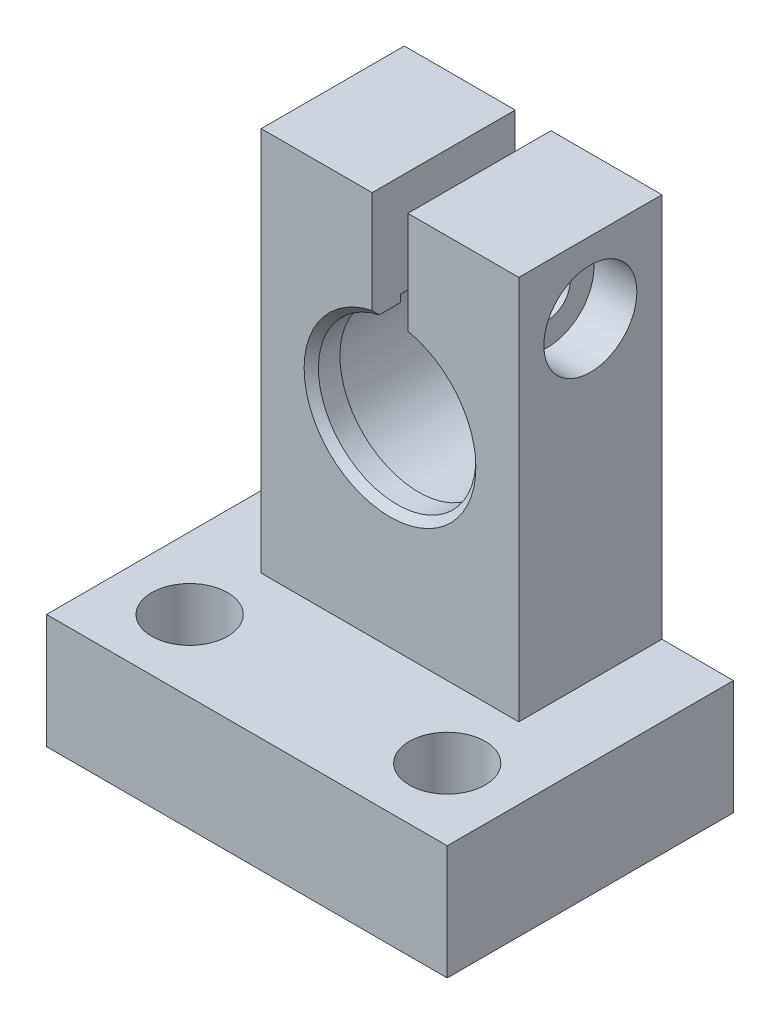
SolidWorks part; units mm, degrees
material "AISI 1045 Steel, cold drawn"
ref_plane "Front Plane" through (0, 0, 0) normal (0, 0, 1) x (1, 0, 0)
ref_plane "Top Plane" through (0, 0, 0) normal (0, 1, 0) x (1, 0, 0)
ref_plane "Right Plane" through (0, 0, 0) normal (1, 0, 0) x (0, 0, -1)
sketch "Sketch1" plane through (0, 0, 0) normal (0, 0, 1) x (1, 0, 0)
  line L1 (9, -21.9) -> (-9, -21.9)
  line L2 (9, -21.9) -> (9, 13)
  line L3 (9, 13) -> (-9, 13)
  line L4 (-9, -21.9) -> (-9, 13)
  line L5 (9, -21.9) -> (-9, 13) construction
  line L6 (9, 13) -> (-9, -21.9) construction
  circle A0 centre (0, 0) radius 6
  point P3 (0, -4.45)
  dimension "D1" = 12
  dimension "D2" = 13
  dimension "D3" = 21.9
  dimension "D4" = 18
extrude "Boss-Extrude1" add sketch "Sketch1" along normal blind 10
sketch "Sketch2" plane through (0, 0, 10) normal (0, 0, -1) x (-1, 0, 0)
  circle A0 centre (0, 0) radius 6 construction
  circle A1 centre (0, 0) radius 6
  circle A2 centre (0, 0) radius 5.5
  dimension "D1" = 0.5
extrude "Boss-Extrude2" add sketch "Sketch2" along normal blind 2
sketch "Sketch3" plane through (0, 0, 10) normal (0, 0, 1) x (1, 0, 0)
  line L0 (9, 13) -> (-9, 13) construction
  line L1 (1.25, 5.3561) -> (-1.25, 5.3561)
  line L2 (1.25, 5.3561) -> (1.25, 13)
  line L3 (1.25, 13) -> (-1.25, 13)
  line L4 (-1.25, 5.3561) -> (-1.25, 13)
  line L5 (1.25, 5.3561) -> (-1.25, 13) construction
  line L6 (1.25, 13) -> (-1.25, 5.3561) construction
  circle A0 centre (0, 0) radius 5.5 construction
  point P0 (0, 9.178)
  dimension "D1" = 2.5
extrude "Cut-Extrude1" cut sketch "Sketch3" against normal through all
hole_wizard "CBORE for M3 SHCS1" positions "Sketch4" profile "Sketch5" counterbore size "M3" standard "ANSI Metric"
sketch "Sketch4" plane through (9, 0, 0) normal (1, 0, 0) x (0, 0, -1)
  line L0 (0, -21.9) -> (0, 13) construction
  line L1 (-10, 13) -> (0, 13) construction
  point P0 (-5, 8)
  dimension "D1" = 5
  dimension "D2" = 5
sketch "Sketch5" plane through (9, 8, 5) normal (0, 1, 0) x (0, 0, -1)
  line L0 (0, 0) -> (0, 7.75)
  line L1 (0, 7.75) -> (1.6, 7.75)
  line L3 (1.6, 7.75) -> (1.6, 3)
  line L4 (1.6, 3) -> (3.25, 3)
  line L5 (3.25, 3) -> (3.25, 0)
  line L7 (3.25, 0) -> (0, 0)
  line L11 (0, -6.35) -> (0, 107.95) construction
  dimension "Thru Hole Dia." = 3.2
  dimension "Thru Hole Depth" = 7.75
  dimension "C'Bore Dia." = 6.5
  dimension "C'Bore Depth" = 3
hole_wizard "Tap Drill for M3x0.5 Tap1" positions "Sketch6" profile "Sketch7" hole size "M3x0.5" standard "ANSI Metric" end condition up to next
sketch "Sketch6" plane through (-9, 0, 0) normal (-1, 0, 0) x (0, 0, 1)
  line L0 (10, 13) -> (10, -21.9) construction
  line L1 (10, 13) -> (0, 13) construction
  point P0 (5, 8)
  dimension "D1" = 5
  dimension "D2" = 5
sketch "Sketch7" plane through (-9, 8, 5) normal (0, 1, 0) x (0, 0, 1)
  line L0 (0, 0) -> (0, 7.75)
  line L1 (0, 7.75) -> (1.25, 7.75)
  line L2 (1.25, 7.75) -> (1.25, 0)
  line L5 (1.25, 0) -> (0, 0)
  line L11 (0, -6.35) -> (0, 107.95) construction
  dimension "Thru Hole Dia." = 2.5
  dimension "Thru Hole Depth" = 7.75
chamfer "Chamfer1" distance 0.5 angle 45 2 edges at (0, -5.5, 10) (0, -6, 0)
sketch "Sketch11" plane through (-9, 0, 0) normal (-1, 0, 0) x (0, 0, 1)
  line L0 (0, 13) -> (0, -21.9) construction
  line L1 (0, -21.9) -> (10, -21.9)
  line L2 (0, -21.9) -> (0, -13.9)
  line L3 (0, -13.9) -> (10, -13.9)
  line L4 (10, -21.9) -> (10, -13.9)
  line L5 (10, 13) -> (10, -21.9) construction
  dimension "D1" = 8
extrude "Boss-Extrude4" add sketch "Sketch11" along normal blind 5
mirror "Mirror1" about plane through (0, 0, 0) normal (1, 0, 0) of "Boss-Extrude4"
sketch "Sketch8" plane through (0, -21.9, 0) normal (0, -1, 0) x (1, 0, 0)
  line L0 (-14, 0) -> (-14, 10) construction
  line L1 (-14, 10) -> (14, 10)
  line L2 (-14, 10) -> (-14, 20)
  line L3 (-14, 20) -> (14, 20)
  line L4 (14, 10) -> (14, 20)
  dimension "D1" = 10
extrude "Boss-Extrude3" add sketch "Sketch8" against normal up to surface (8 mm away) up to face at (-11.5, -13.9, 5)
hole_wizard "M5 Clearance Hole1" positions "Sketch9" profile "Sketch10" hole size "M5" standard "ANSI Metric" end condition up to next
sketch "Sketch9" plane through (0, -13.9, 0) normal (0, 1, 0) x (1, 0, 0)
  line L0 (14, -20) -> (-14, -20) construction
  line L1 (-14, -20) -> (-14, 0) construction
  line L2 (0, -10) -> (0, -20) construction
  line L4 (-9, -10) -> (9, -10) construction
  point P0 (-9, -15)
  point P14 (9, -15)
  dimension "D1" = 5
  dimension "D2" = 5
sketch "Sketch10" plane through (-9, -13.9, 15) normal (1, 0, 0) x (0, 0, 1)
  line L0 (0, 0) -> (0, 8)
  line L1 (0, 8) -> (2.65, 8)
  line L2 (2.65, 8) -> (2.65, 0)
  line L5 (2.65, 0) -> (0, 0)
  line L11 (0, -6.35) -> (0, 107.95) construction
  dimension "Thru Hole Dia." = 5.3
  dimension "Thru Hole Depth" = 8
